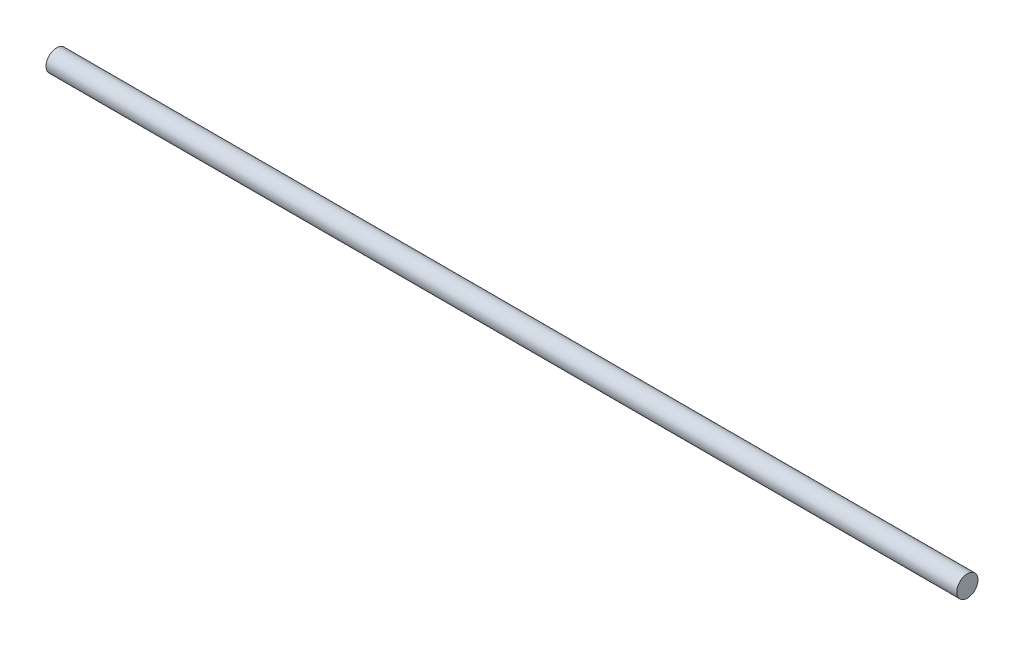
SolidWorks part; units mm, degrees
material "1023 碳钢板 (SS)"
ref_plane "前视基准面" through (0, 0, 0) normal (0, 0, 1) x (1, 0, 0)
ref_plane "上视基准面" through (0, 0, 0) normal (0, 1, 0) x (1, 0, 0)
ref_plane "右视基准面" through (0, 0, 0) normal (1, 0, 0) x (0, 0, -1)
other "Configuration Table"
sketch "草图1" plane through (0, 0, 0) normal (1, 0, 0) x (0, 0, -1)
  circle A0 centre (0, 0) radius 4
  dimension "D1" = 8
extrude "凸台-拉伸1" add sketch "草图1" along normal mid plane 383
sketch "草图2" plane through (0, 0, 0) normal (0, 0, 1) x (1, 0, 0)
  line L0 (-1000, 0) -> (49000, 0) construction
  line L1 (191.5, -4) -> (191.5, 4) construction
  line L2 (-175.5, -4) -> (-191.5, -4)
  line L3 (-175.5, -4) -> (-175.5, 4)
  line L4 (-175.5, 4) -> (-191.5, 4)
  line L5 (-191.5, -4) -> (-191.5, 4)
  line L6 (-175.5, -4) -> (-191.5, 4) construction
  line L7 (-175.5, 4) -> (-191.5, -4) construction
  line L8 (175.5, -4) -> (191.5, -4)
  line L9 (175.5, -4) -> (175.5, 4)
  line L10 (175.5, 4) -> (191.5, 4)
  line L11 (191.5, -4) -> (191.5, 4)
  line L12 (175.5, -4) -> (191.5, 4) construction
  line L13 (175.5, 4) -> (191.5, -4) construction
  point P1 (-183.5, 0)
  point P9 (183.5, 0)
  dimension "D1" = 16
  dimension "D2" = 16
sketch "草图3" plane through (-191.5, 0, 0) normal (-1, 0, 0) x (0, 0, 1)
  circle A1 centre (0, 0) radius 4
  circle A2 centre (0, 0) radius 4
  dimension "D1" = 0
sketch "草图4" plane through (191.5, 0, 0) normal (1, 0, 0) x (0, 0, -1)
  circle A1 centre (0, 0) radius 4
  circle A2 centre (0, 0) radius 4
  dimension "D1" = 0
extrude "切除-拉伸2" cut sketch "草图4" against normal blind 40
